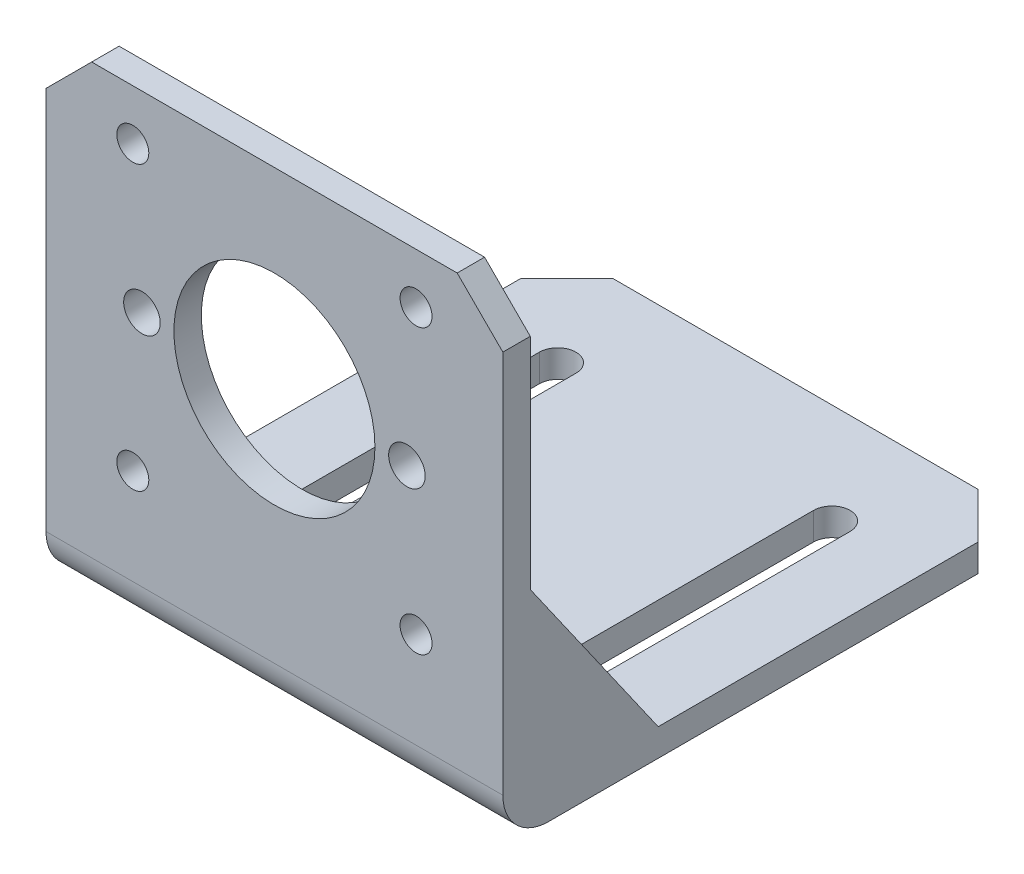
SolidWorks part; units mm, degrees
ref_plane "前基準面" through (0, 0, 0) normal (0, 0, 1) x (1, 0, 0)
ref_plane "上基準面" through (0, 0, 0) normal (0, 1, 0) x (1, 0, 0)
ref_plane "右基準面" through (0, 0, 0) normal (1, 0, 0) x (0, 0, -1)
sketch "草圖1" plane through (0, 0, 0) normal (0, 0, 1) x (1, 0, 0)
  line L1 (-25, 26) -> (25, 26)
  line L2 (-25, 26) -> (-25, -26)
  line L3 (-25, -26) -> (25, -26)
  line L4 (25, 26) -> (25, -26)
  point P4 (0, 26)
  point P6 (-25, 0)
  dimension "D1" = 50
  dimension "D2" = 52
extrude "填料-伸長1" add sketch "草圖1" along normal blind 3
sketch "草圖2" plane through (0, 0, 0) normal (0, 0, -1) x (-1, 0, 0)
  line L0 (25, 26) -> (25, -26) construction
  line L1 (-25, -26) -> (25, -26)
  line L2 (-25, -26) -> (-25, -23)
  line L3 (-25, -23) -> (25, -23)
  line L4 (25, -26) -> (25, -23)
  dimension "D1" = 3
extrude "填料-伸長2" add sketch "草圖2" along normal blind 54
sketch "草圖3" plane through (0, 0, 3) normal (0, 0, 1) x (1, 0, 0)
  line L0 (25, 26) -> (-25, 26) construction
  line L1 (0, 16) -> (0, -6) construction
  line L2 (0, 5) -> (-15.5, 5) construction
  line L3 (-15.5, 5) -> (-15.5, -10.5) construction
  circle A0 centre (0, 5) radius 11
  circle A1 centre (14.5, 5) radius 2
  circle A2 centre (-14.5, 5) radius 2
  circle A3 centre (-15.5, -10.5) radius 1.75
  circle A4 centre (-15.5, 20.5) radius 1.75
  circle A5 centre (15.5, 20.5) radius 1.75
  circle A6 centre (15.5, -10.5) radius 1.75
  point P22 (0, 5)
  dimension "D1" = 22
  dimension "D3" = 4
  dimension "D7" = 3.5
  dimension "D2" = 21
  dimension "D4" = 14.5
  dimension "D5" = 15.5
  dimension "D6" = 15.5
  dimension "D8" = 4
extrude "除料-伸長1" cut sketch "草圖3" against normal through all
chamfer "導角1" distance 5 angle 45 2 edges at (-25, 26, 1.5) (25, 26, 1.5)
chamfer "導角2" distance 5 angle 45 2 edges at (-25, -24.5, -54) (25, -24.5, -54)
sketch "草圖4" plane through (0, -26, 0) normal (0, -1, 0) x (1, 0, 0)
  line L0 (15, -43) -> (15, -13) construction
  line L1 (13, -43) -> (13, -13)
  line L2 (17, -43) -> (17, -13)
  line L3 (0, 3) -> (0, -54) construction
  line L4 (-25, 3) -> (25, 3) construction
  line L5 (20, -54) -> (-20, -54) construction
  line L6 (25, 3) -> (25, -49) construction
  line L7 (-15, -43) -> (-15, -13) construction
  line L8 (-13, -43) -> (-13, -13)
  line L9 (-17, -43) -> (-17, -13)
  arc A0 (13, -43) -> (17, -43) centre (15, -43) ccw
  arc A1 (17, -13) -> (13, -13) centre (15, -13) ccw
  arc A2 (-13, -43) -> (-17, -43) centre (-15, -43) cw
  arc A3 (-17, -13) -> (-13, -13) centre (-15, -13) cw
  point P2 (15, -28)
  point P17 (-15, -28)
  dimension "D1" = 4
  dimension "D2" = 11
  dimension "D3" = 30
  dimension "D4" = 10
  dimension "D5" = 15
  dimension "D6" = 30
extrude "除料-伸長2" cut sketch "草圖4" against normal through all
sketch "草圖5" plane through (25, 0, 0) normal (1, 0, 0) x (0, 0, -1)
  line L0 (0, -23) -> (0, -3)
  line L1 (0, -23) -> (0, 21) construction
  line L2 (0, -3) -> (14, -23)
  line L3 (49, -23) -> (0, -23) construction
  line L4 (14, -23) -> (0, -23)
  dimension "D1" = 20
  dimension "D2" = 14
extrude "填料-伸長3" add sketch "草圖5" against normal up to surface (50 mm away)
sketch "草圖6" plane through (25, 0, 0) normal (1, 0, 0) x (0, 0, -1)
  line L0 (0, -3) -> (14, -23)
  line L1 (14, -23) -> (0, -23)
  line L2 (0, -23) -> (0, -3)
extrude "除料-伸長3" cut sketch "草圖6" against normal blind 44 from offset 3 offset against normal yes
fillet "圓角1" radius 5 1 edges at (0, -26, 3)
